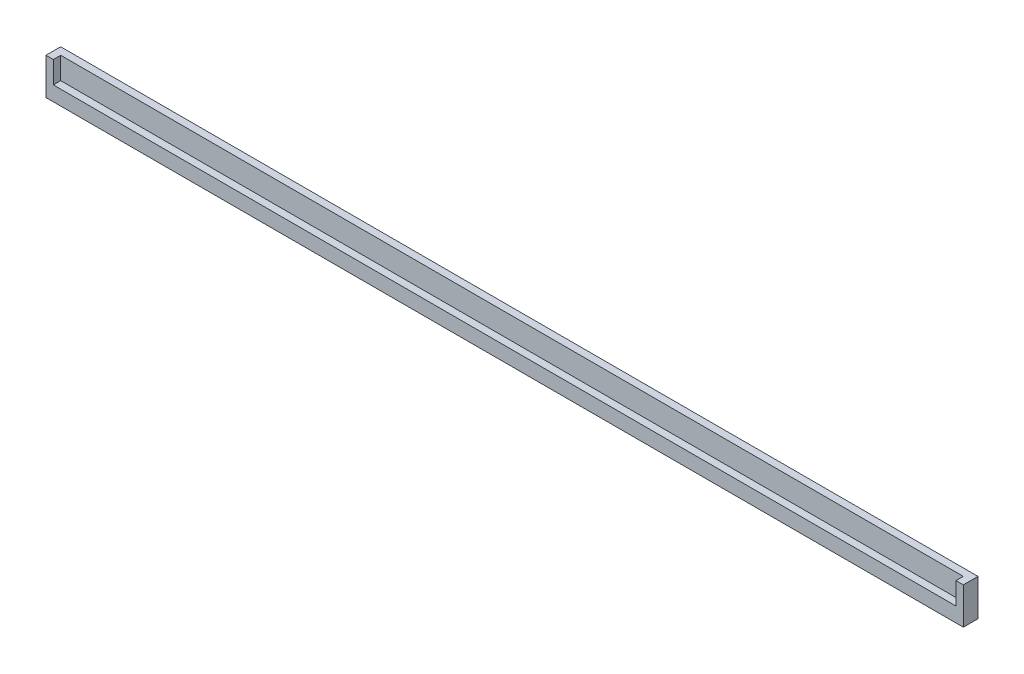
SolidWorks part; units mm, degrees
ref_plane "Plan de face" through (0, 0, 0) normal (0, 0, 1) x (1, 0, 0)
ref_plane "Plan de dessus" through (0, 0, 0) normal (0, 1, 0) x (1, 0, 0)
ref_plane "Plan de droite" through (0, 0, 0) normal (1, 0, 0) x (0, 0, -1)
sketch "Esquisse1" plane through (0, 0, 0) normal (0, 0, 1) x (1, 0, 0)
  line L1 (-115.3852, 5.6749) -> (384.6148, 5.6749)
  line L2 (-115.3852, 5.6749) -> (-115.3852, -14.3251)
  line L3 (-115.3852, -14.3251) -> (384.6148, -14.3251)
  line L4 (384.6148, 5.6749) -> (384.6148, -14.3251)
extrude "Boss.-Extru.1" add sketch "Esquisse1" along normal blind 8
sketch "Esquisse2" plane through (0, 0, 8) normal (0, 0, 1) x (1, 0, 0)
  line L0 (384.6148, 5.6749) -> (-115.3852, 5.6749) construction
  line L1 (-111.3852, 5.6749) -> (380.6148, 5.6749)
  line L2 (-111.3852, 5.6749) -> (-111.3852, -6.3251)
  line L3 (-111.3852, -6.3251) -> (380.6148, -6.3251)
  line L4 (380.6148, 5.6749) -> (380.6148, -6.3251)
  line L5 (-115.3852, 5.6749) -> (-115.3852, -14.3251) construction
  line L6 (384.6148, -14.3251) -> (384.6148, 5.6749) construction
  dimension "D1" = 4
  dimension "D2" = 4
  dimension "D3" = 12
extrude "Enlèv. mat.-Extru.1" cut sketch "Esquisse2" against normal blind 4
